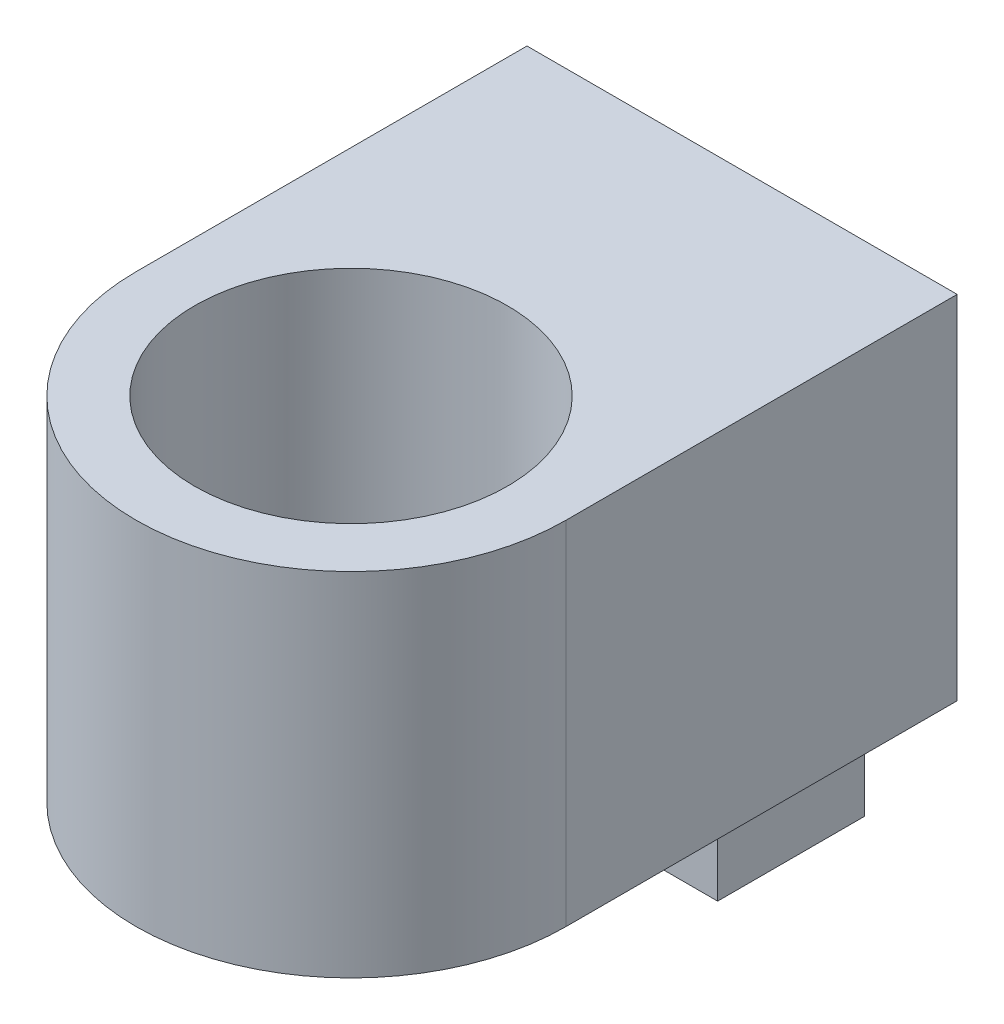
SolidWorks part; units mm, degrees
ref_plane "Front Plane" through (0, 0, 0) normal (0, 0, 1) x (1, 0, 0)
ref_plane "Top Plane" through (0, 0, 0) normal (0, 1, 0) x (1, 0, 0)
ref_plane "Right Plane" through (0, 0, 0) normal (1, 0, 0) x (0, 0, -1)
sketch "Sketch1" plane through (0, 0, 0) normal (0, 1, 0) x (1, 0, 0)
  line L0 (-11, 0) -> (-11, 20)
  line L1 (11, 0) -> (11, 20)
  line L2 (-11, 20) -> (11, 20)
  circle A0 centre (0, 0) radius 8
  arc A1 (-11, 0) -> (11, 0) centre (0, 0) ccw
  dimension "D1" = 16
  dimension "D2" = 22
  dimension "D3" = 20
extrude "Boss-Extrude1" add sketch "Sketch1" along normal blind 18
sketch "Sketch2" plane through (0, 0, -20) normal (0, 0, -1) x (-1, 0, 0)
  line L0 (-11, 18) -> (11, 0) construction
  line L1 (-11, 0) -> (11, 18) construction
  circle A0 centre (0, 9) radius 6
  dimension "D1" = 12
extrude "Cut-Extrude1" cut sketch "Sketch2" against normal blind 10
sketch "Sketch3" plane through (0, 18, 0) normal (0, 1, 0) x (1, 0, 0)
  line L0 (-11, 13.7953) -> (-8.75, 13.7953) construction
  line L1 (-8.75, 17.5) -> (8.75, 17.5)
  line L2 (-8.75, 17.5) -> (-8.75, 10)
  line L3 (-8.75, 10) -> (8.75, 10)
  line L4 (8.75, 17.5) -> (8.75, 10)
  line L5 (-11, 20) -> (-11, 0) construction
  line L6 (8.75, 13.7953) -> (11, 13.7953) construction
  line L7 (11, 0) -> (11, 20) construction
  line L8 (-5.9436, 17.5) -> (-5.9436, 20) construction
  line L9 (11, 20) -> (-11, 20) construction
  dimension "D1" = 7.5
  dimension "D2" = 17.5
  dimension "D3" = 2.5
sketch "Sketch4" plane through (0, 0, 0) normal (0, -1, 0) x (1, 0, 0)
  line L1 (-8.75, -10) -> (8.75, -10)
  line L2 (-8.75, -10) -> (-8.75, -17.5)
  line L3 (-8.75, -17.5) -> (8.75, -17.5)
  line L4 (8.75, -10) -> (8.75, -17.5)
extrude "Boss-Extrude3" add sketch "Sketch4" along normal blind 5
